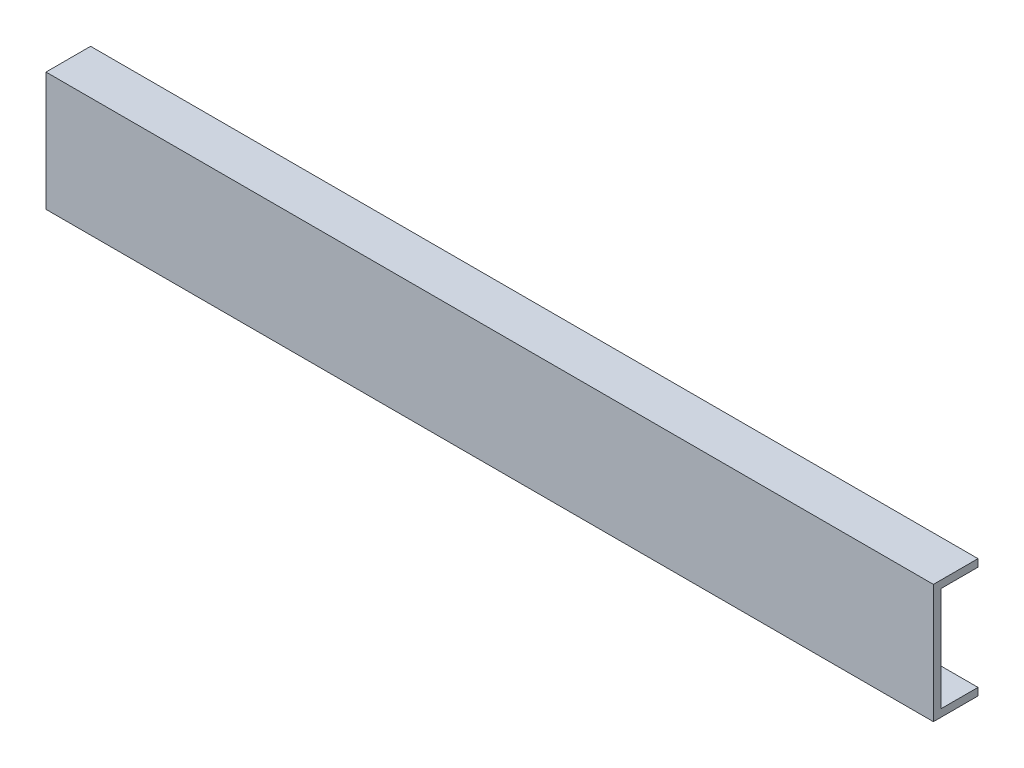
SolidWorks part; units mm, degrees
ref_plane "Front Plane" through (0, 0, 0) normal (0, 0, 1) x (1, 0, 0)
ref_plane "Top Plane" through (0, 0, 0) normal (0, 1, 0) x (1, 0, 0)
ref_plane "Right Plane" through (0, 0, 0) normal (1, 0, 0) x (0, 0, -1)
sketch "Sketch1" plane through (0, 0, 0) normal (1, 0, 0) x (0, 0, -1)
  line L0 (0, 65.8376) -> (30, 65.8376)
  line L1 (30, 65.8376) -> (30, 60.8376)
  line L2 (30, 60.8376) -> (5, 60.8376)
  line L3 (5, 60.8376) -> (5, -9.1624)
  line L4 (5, -9.1624) -> (30, -9.1624)
  line L5 (30, -9.1624) -> (30, -14.1624)
  line L6 (30, -14.1624) -> (0, -14.1624)
  line L7 (0, -14.1624) -> (0, 65.8376)
  dimension "D1" = 5
  dimension "D2" = 80
  dimension "D3" = 5
  dimension "D4" = 30
extrude "Boss-Extrude1" add sketch "Sketch1" along normal blind 596.9
